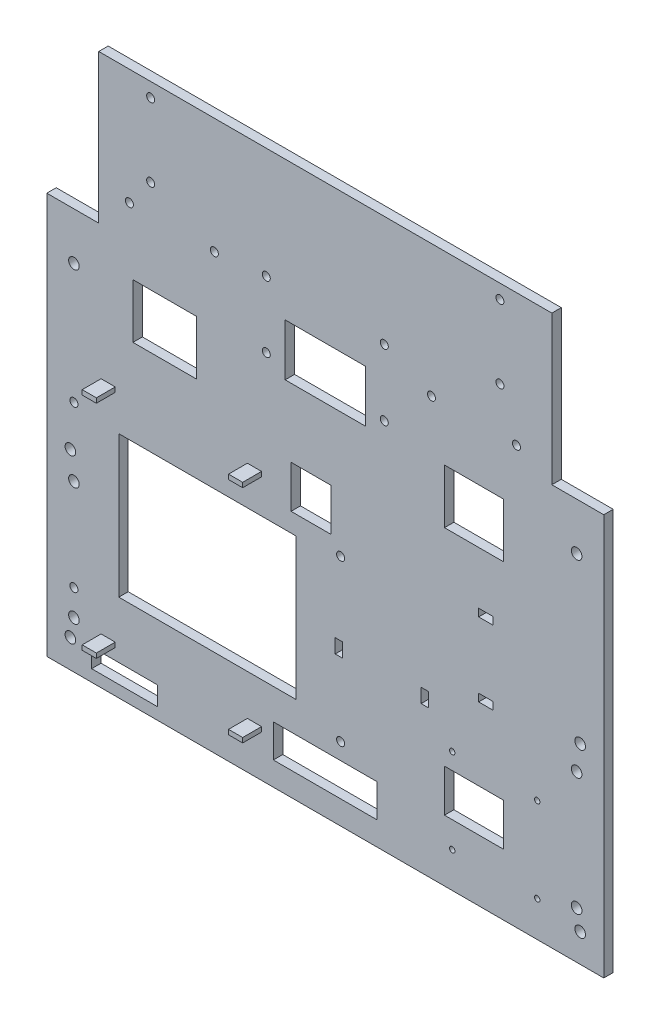
SolidWorks part; units mm, degrees
ref_plane "前视基准面" through (0, 0, 0) normal (0, 0, 1) x (1, 0, 0)
ref_plane "上视基准面" through (0, 0, 0) normal (0, 1, 0) x (1, 0, 0)
ref_plane "右视基准面" through (0, 0, 0) normal (1, 0, 0) x (0, 0, -1)
other "Configuration Table"
sketch "Sketch_Equipment_deck" plane through (0, 0, 0) normal (0, 0, 1) x (1, 0, 0)
  line L0 (118, 85) -> (118, -85)
  line L1 (118, -85) -> (-118, -85)
  line L2 (-118, -85) -> (-118, 85)
  line L3 (-118, 85) -> (-96, 85)
  line L4 (-96, 85) -> (-96, 148)
  line L5 (-96, 148) -> (96, 148)
  line L6 (96, 148) -> (96, 85)
  line L7 (96, 85) -> (118, 85)
extrude "Equipment_deck" add sketch "Sketch_Equipment_deck" along normal blind 4 from offset 32
sketch "Sketch_Equipment_and_cable_windows" plane through (0, 0, 0) normal (0, 0, 1) x (1, 0, 0)
  line L0 (-71, -72) -> (-71, -80)
  line L1 (-71, -80) -> (-99, -80)
  line L2 (-99, -80) -> (-99, -72)
  line L3 (-99, -72) -> (-71, -72)
  line L4 (22, -61) -> (22, -75)
  line L5 (22, -75) -> (-22, -75)
  line L6 (-22, -75) -> (-22, -61)
  line L7 (-22, -61) -> (22, -61)
  line L8 (75.5, -41) -> (75.5, -59)
  line L9 (75.5, -59) -> (50.5, -59)
  line L10 (50.5, -59) -> (50.5, -41)
  line L11 (50.5, -41) -> (75.5, -41)
  line L12 (-12.5, 12) -> (-12.5, -48)
  line L13 (-12.5, -48) -> (-87.5, -48)
  line L14 (-87.5, -48) -> (-87.5, 12)
  line L15 (-87.5, 12) -> (-12.5, 12)
  line L16 (2.5, 38) -> (2.5, 20)
  line L17 (2.5, 20) -> (-14.5, 20)
  line L18 (-14.5, 20) -> (-14.5, 38)
  line L19 (-14.5, 38) -> (2.5, 38)
  line L20 (75.5, 69.5) -> (75.5, 46.5)
  line L21 (75.5, 46.5) -> (50.5, 46.5)
  line L22 (50.5, 46.5) -> (50.5, 69.5)
  line L23 (50.5, 69.5) -> (75.5, 69.5)
  line L24 (-54.5, 71.5) -> (-54.5, 48.5)
  line L25 (-54.5, 48.5) -> (-81.5, 48.5)
  line L26 (-81.5, 48.5) -> (-81.5, 71.5)
  line L27 (-81.5, 71.5) -> (-54.5, 71.5)
  line L28 (17, 89) -> (17, 67)
  line L29 (17, 67) -> (-17, 67)
  line L30 (-17, 67) -> (-17, 89)
  line L31 (-17, 89) -> (17, 89)
extrude "Equipment_and_cable_windows" cut sketch "Sketch_Equipment_and_cable_windows" along normal blind 6 from offset 31
sketch "Sketch_Chassis_M4" plane through (0, 0, 0) normal (0, 0, 1) x (1, 0, 0)
  circle A0 centre (-106.5, -65) radius 2.25
  circle A1 centre (-106.5, -15) radius 2.25
  circle A2 centre (-106.5, 65) radius 2.25
  circle A3 centre (106.5, -65) radius 2.25
  circle A4 centre (106.5, -15) radius 2.25
  circle A5 centre (106.5, 65) radius 2.25
  dimension "D1" = 4.5
  dimension "D4" = 4.5
  dimension "D7" = 4.5
  dimension "D10" = 4.5
  dimension "D13" = 4.5
  dimension "D16" = 4.5
  dimension "D2" = 106.5
  dimension "D3" = 65
  dimension "D5" = 106.5
  dimension "D6" = 15
  dimension "D8" = 106.5
  dimension "D9" = 65
  dimension "D11" = 106.5
  dimension "D12" = 65
  dimension "D14" = 106.5
  dimension "D15" = 15
  dimension "D17" = 106.5
  dimension "D18" = 65
extrude "Chassis_M4" cut sketch "Sketch_Chassis_M4" along normal blind 6 from offset 31
sketch "Sketch_MID_posts_M4" plane through (0, 0, 0) normal (0, 0, 1) x (1, 0, 0)
  circle A0 centre (-108, -73) radius 2.25
  circle A1 centre (-108, -4) radius 2.25
  circle A2 centre (108, -73) radius 2.25
  circle A3 centre (108, -4) radius 2.25
  dimension "D1" = 4.5
  dimension "D4" = 4.5
  dimension "D7" = 4.5
  dimension "D10" = 4.5
  dimension "D2" = 108
  dimension "D3" = 73
  dimension "D5" = 108
  dimension "D6" = 4
  dimension "D8" = 108
  dimension "D9" = 73
  dimension "D11" = 108
  dimension "D12" = 4
extrude "MID_posts_M4" cut sketch "Sketch_MID_posts_M4" along normal blind 6 from offset 31
sketch "Sketch_Jetson_clamps_M3" plane through (0, 0, 0) normal (0, 0, 1) x (1, 0, 0)
  circle A0 centre (-106.5, -54) radius 1.7
  circle A1 centre (-106.5, 14) radius 1.7
  circle A2 centre (6.5, -54) radius 1.7
  circle A3 centre (6.5, 14) radius 1.7
  dimension "D1" = 3.4
  dimension "D4" = 3.4
  dimension "D7" = 3.4
  dimension "D10" = 3.4
  dimension "D2" = 106.5
  dimension "D3" = 54
  dimension "D5" = 106.5
  dimension "D6" = 14
  dimension "D8" = 6.5
  dimension "D9" = 54
  dimension "D11" = 6.5
  dimension "D12" = 14
extrude "Jetson_clamps_M3" cut sketch "Sketch_Jetson_clamps_M3" along normal blind 6 from offset 31
sketch "Sketch_MC02_M2" plane through (0, 0, 0) normal (0, 0, 1) x (1, 0, 0)
  circle A0 centre (53.8, -70) radius 1.15
  circle A1 centre (53.8, -34) radius 1.15
  circle A2 centre (89.8, -70) radius 1.15
  circle A3 centre (89.8, -34) radius 1.15
  dimension "D1" = 2.3
  dimension "D4" = 2.3
  dimension "D7" = 2.3
  dimension "D10" = 2.3
  dimension "D2" = 53.8
  dimension "D3" = 70
  dimension "D5" = 53.8
  dimension "D6" = 34
  dimension "D8" = 89.8
  dimension "D9" = 70
  dimension "D11" = 89.8
  dimension "D12" = 34
extrude "MC02_M2" cut sketch "Sketch_MC02_M2" along normal blind 6 from offset 31
sketch "Sketch_XT_posts_M3" plane through (0, 0, 0) normal (0, 0, 1) x (1, 0, 0)
  circle A0 centre (-25, 73) radius 1.7
  circle A1 centre (-25, 101) radius 1.7
  circle A2 centre (25, 73) radius 1.7
  circle A3 centre (25, 101) radius 1.7
  dimension "D1" = 3.4
  dimension "D4" = 3.4
  dimension "D7" = 3.4
  dimension "D10" = 3.4
  dimension "D2" = 25
  dimension "D3" = 73
  dimension "D5" = 25
  dimension "D6" = 101
  dimension "D8" = 25
  dimension "D9" = 73
  dimension "D11" = 25
  dimension "D12" = 101
extrude "XT_posts_M3" cut sketch "Sketch_XT_posts_M3" along normal blind 6 from offset 31
sketch "Sketch_Driver_trays_M3" plane through (0, 0, 0) normal (0, 0, 1) x (1, 0, 0)
  circle A0 centre (-83, 99) radius 1.7
  circle A1 centre (-47, 99) radius 1.7
  circle A2 centre (45, 92) radius 1.7
  circle A3 centre (81, 92) radius 1.7
  dimension "D1" = 3.4
  dimension "D4" = 3.4
  dimension "D7" = 3.4
  dimension "D10" = 3.4
  dimension "D2" = 83
  dimension "D3" = 99
  dimension "D5" = 47
  dimension "D6" = 99
  dimension "D8" = 45
  dimension "D9" = 92
  dimension "D11" = 81
  dimension "D12" = 92
extrude "Driver_trays_M3" cut sketch "Sketch_Driver_trays_M3" along normal blind 6 from offset 31
sketch "Sketch_Camera_M3" plane through (0, 0, 0) normal (0, 0, 1) x (1, 0, 0)
  circle A0 centre (-74, 111) radius 1.7
  circle A1 centre (-74, 142) radius 1.7
  circle A2 centre (74, 111) radius 1.7
  circle A3 centre (74, 142) radius 1.7
  dimension "D1" = 3.4
  dimension "D4" = 3.4
  dimension "D7" = 3.4
  dimension "D10" = 3.4
  dimension "D2" = 74
  dimension "D3" = 111
  dimension "D5" = 74
  dimension "D6" = 142
  dimension "D8" = 74
  dimension "D9" = 111
  dimension "D11" = 74
  dimension "D12" = 142
extrude "Camera_M3" cut sketch "Sketch_Camera_M3" along normal blind 6 from offset 31
sketch "Sketch_Logic_and_FFC_strap_slots" plane through (0, 0, 0) normal (0, 0, 1) x (1, 0, 0)
  line L0 (4.2, -17) -> (7.4, -17)
  line L1 (7.4, -17) -> (7.4, -23)
  line L2 (7.4, -23) -> (4.2, -23)
  line L3 (4.2, -23) -> (4.2, -17)
  line L4 (40.6, -17) -> (43.8, -17)
  line L5 (43.8, -17) -> (43.8, -23)
  line L6 (43.8, -23) -> (40.6, -23)
  line L7 (40.6, -23) -> (40.6, -17)
  line L8 (65, -7) -> (71, -7)
  line L9 (71, -7) -> (71, -10.2)
  line L10 (71, -10.2) -> (65, -10.2)
  line L11 (65, -10.2) -> (65, -7)
  line L12 (65, 24.2) -> (71, 24.2)
  line L13 (71, 24.2) -> (71, 21)
  line L14 (71, 21) -> (65, 21)
  line L15 (65, 21) -> (65, 24.2)
extrude "Logic_and_FFC_strap_slots" cut sketch "Sketch_Logic_and_FFC_strap_slots" along normal blind 6 from offset 31
sketch "Sketch_Jetson_longitudinal_stops" plane through (0, 0, 0) normal (0, 0, 1) x (1, 0, 0)
  line L0 (-95, -65.25) -> (-89, -65.25)
  line L1 (-89, -65.25) -> (-89, -67.25)
  line L2 (-89, -67.25) -> (-95, -67.25)
  line L3 (-95, -67.25) -> (-95, -65.25)
  line L4 (-33, -65.25) -> (-27, -65.25)
  line L5 (-27, -65.25) -> (-27, -67.25)
  line L6 (-27, -67.25) -> (-33, -67.25)
  line L7 (-33, -67.25) -> (-33, -65.25)
  line L8 (-95, 28.4) -> (-89, 28.4)
  line L9 (-89, 28.4) -> (-89, 26.4)
  line L10 (-89, 26.4) -> (-95, 26.4)
  line L11 (-95, 26.4) -> (-95, 28.4)
  line L12 (-33, 28.4) -> (-27, 28.4)
  line L13 (-27, 28.4) -> (-27, 26.4)
  line L14 (-27, 26.4) -> (-33, 26.4)
  line L15 (-33, 26.4) -> (-33, 28.4)
extrude "Jetson_longitudinal_stops" add sketch "Sketch_Jetson_longitudinal_stops" along normal blind 8 from offset 36
